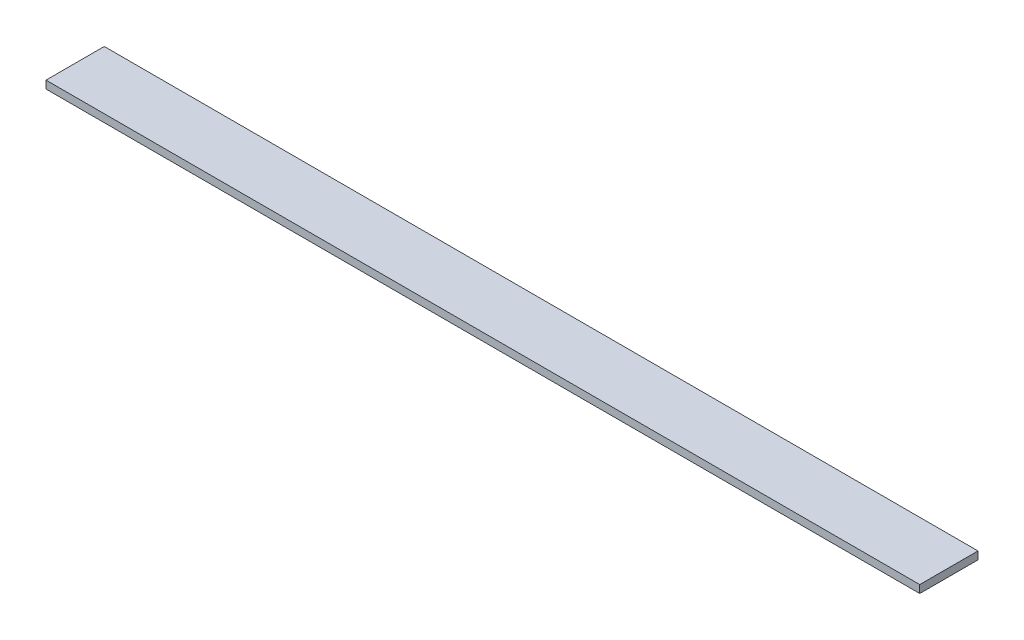
SolidWorks part; units mm, degrees
ref_plane "前基準面" through (0, 0, 0) normal (0, 0, 1) x (1, 0, 0)
ref_plane "上基準面" through (0, 0, 0) normal (0, 1, 0) x (1, 0, 0)
ref_plane "右基準面" through (0, 0, 0) normal (1, 0, 0) x (0, 0, -1)
sketch "草圖1" plane through (0, 0, 0) normal (0, 1, 0) x (1, 0, 0)
  line L0 (0, 0) -> (450, 0)
  line L1 (450, 0) -> (450, 30)
  line L2 (450, 30) -> (0, 30)
  line L3 (0, 30) -> (0, 0)
  dimension "D1" = 30
  dimension "D2" = 450
extrude "填料-伸長1" add sketch "草圖1" along normal blind 4
